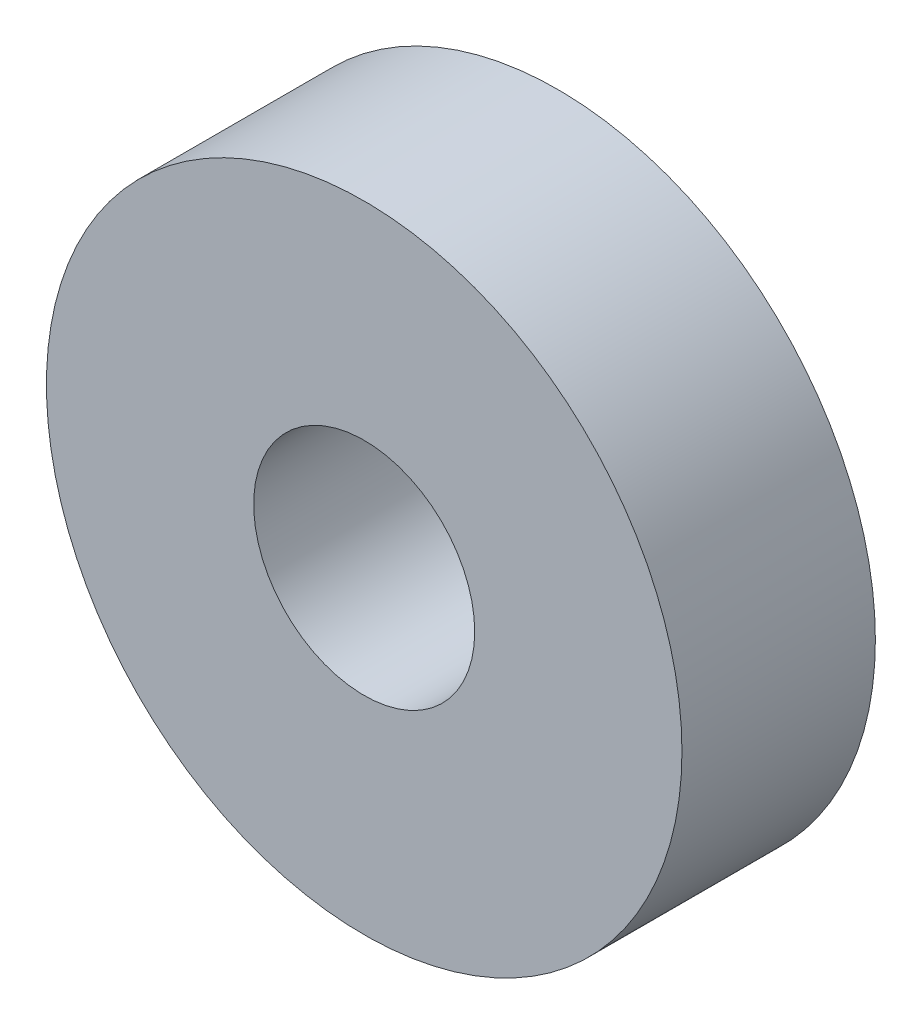
SolidWorks part; units mm, degrees
material "PTFE (general)"
ref_plane "Front Plane" through (0, 0, 0) normal (0, 0, 1) x (1, 0, 0)
ref_plane "Top Plane" through (0, 0, 0) normal (0, 1, 0) x (1, 0, 0)
ref_plane "Right Plane" through (0, 0, 0) normal (1, 0, 0) x (0, 0, -1)
sketch "Sketch1" plane through (0, 0, 0) normal (0, 0, 1) x (1, 0, 0)
  circle A0 centre (0, 0) radius 11.5
  circle A1 centre (0, 0) radius 4
  dimension "D1" = 8
  dimension "D2" = 23
extrude "Boss-Extrude1" add sketch "Sketch1" along normal blind 7
ref_plane "Plane1" through (0, 0, 3.5) normal (0, 0, 1) x (1, 0, 0)
